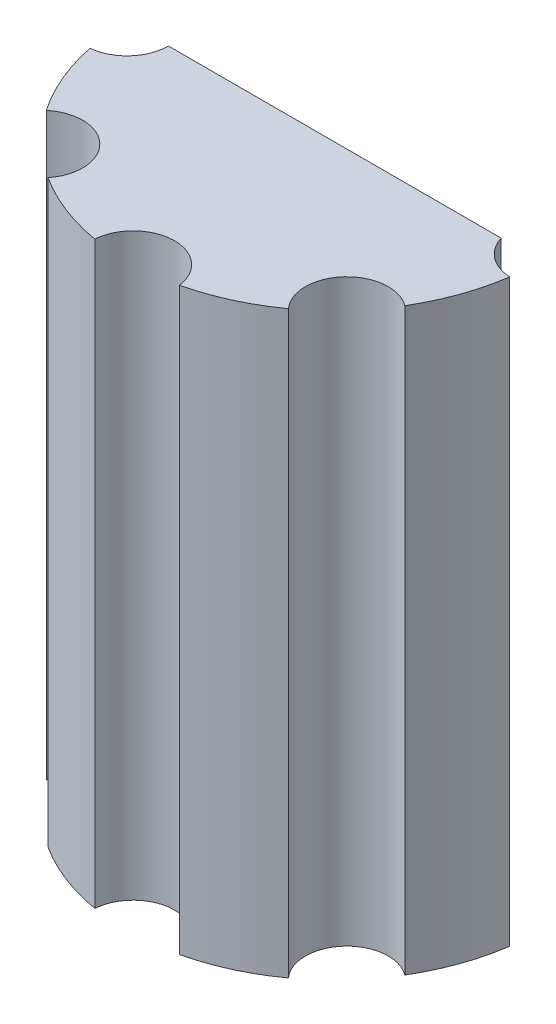
SolidWorks part; units mm, degrees
ref_plane "Front Plane" through (0, 0, 0) normal (0, 0, 1) x (1, 0, 0)
ref_plane "Top Plane" through (0, 0, 0) normal (0, 1, 0) x (1, 0, 0)
ref_plane "Right Plane" through (0, 0, 0) normal (1, 0, 0) x (0, 0, -1)
sketch "Sketch1" plane through (0, 0, 0) normal (0, 1, 0) x (1, 0, 0)
  line L0 (-2.5, 0) -> (2.5, 0)
  arc A0 (-2.5, 0) -> (2.5, 0) centre (0, 0) ccw
  dimension "D1" = 2.5
extrude "Boss-Extrude2" add sketch "Sketch1" along normal blind 7
sketch "Sketch3" plane through (0, 0, 0) normal (0, 1, 0) x (1, 0, 0)
  line L0 (2.5, 0) -> (-2.5, 0) construction
  line L1 (0, 0) -> (-2.5, 0) construction
  circle A0 centre (-2.5, 0) radius 0.5
  arc A1 (-2.5, 0) -> (2.5, 0) centre (0, 0) ccw construction
  circle A2 centre (-1.7418, -1.7934) radius 0.5
  circle A3 centre (0.073, -2.4989) radius 0.5
  circle A4 centre (1.8435, -1.6887) radius 0.5
  circle A5 centre (2.4957, 0.1459) radius 0.5
  dimension "D1" = 1
  dimension "D3" = 45.837
  dimension "D4" = 5
extrude "Cut-Extrude3" cut sketch "Sketch3" along normal through all
